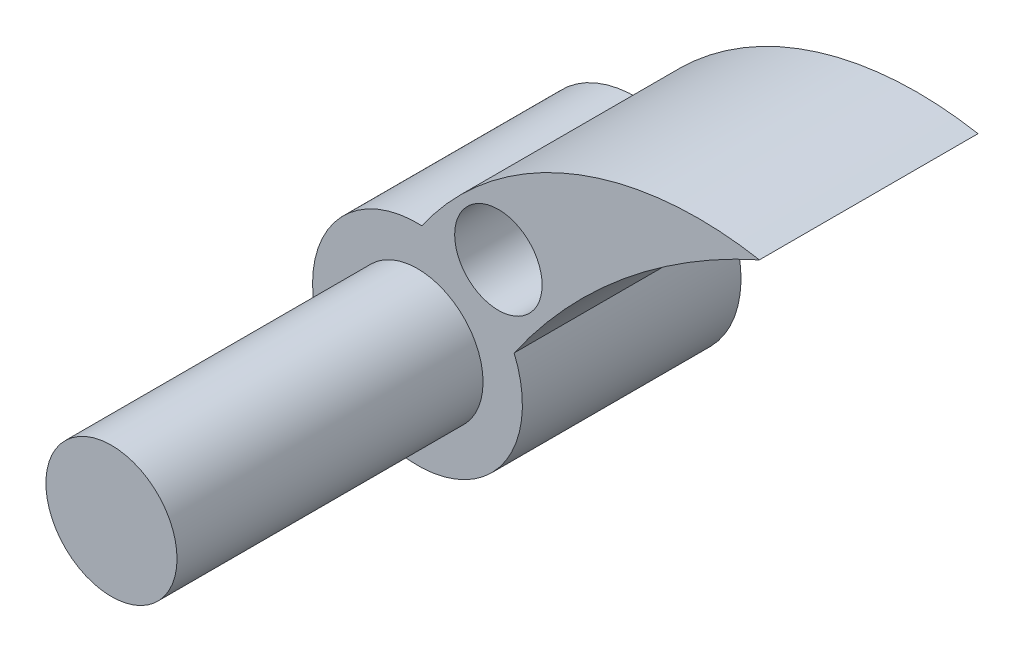
SolidWorks part; units mm, degrees
material "Plain Carbon Steel"
ref_plane "Front" through (0, 0, 0) normal (0, 0, 1) x (1, 0, 0)
ref_plane "Top" through (0, 0, 0) normal (0, 1, 0) x (1, 0, 0)
ref_plane "Right" through (0, 0, 0) normal (1, 0, 0) x (0, 0, -1)
sketch "Sketch1" plane through (0, 0, 0) normal (0, 0, 1) x (1, 0, 0)
  line L0 (18.2693, -1.3942) -> (-14897.9642, 10357.1012) construction
  arc A0 (12.7354, 10.9937) -> (5.0163, 7.8092) centre (11.3462, 3.4135) ccw
  arc A1 (12.7354, 10.9937) -> (7.1251, 6.3448) centre (18.2693, -1.3942) ccw
  arc A2 (5.0163, 7.8092) -> (7.1251, 6.3448) centre (4.914, 5.4114) ccw
  dimension "D1" = 2.4
extrude "Boss-Extrude1" add sketch "Sketch1" along normal blind 5
sketch "Sketch2" plane through (0, 0, 5) normal (0, 0, 1) x (1, 0, 0)
  line L0 (5.0163, 7.8092) -> (7.1251, 6.3448) construction
  circle A0 centre (4.914, 5.4114) radius 1.5
  arc A1 (5.0163, 7.8092) -> (7.1251, 6.3448) centre (4.914, 5.4114) ccw construction
  dimension "D1" = 3
extrude "Boss-Extrude2" add sketch "Sketch2" along normal blind 7
sketch "Sketch4" plane through (0, 0, 0) normal (0, 0, -1) x (-1, 0, 0)
  circle A0 centre (-6.7645, 8.0091) radius 1
  dimension "D1" = 2
extrude "Cut-Extrude1" cut sketch "Sketch4" against normal through all
